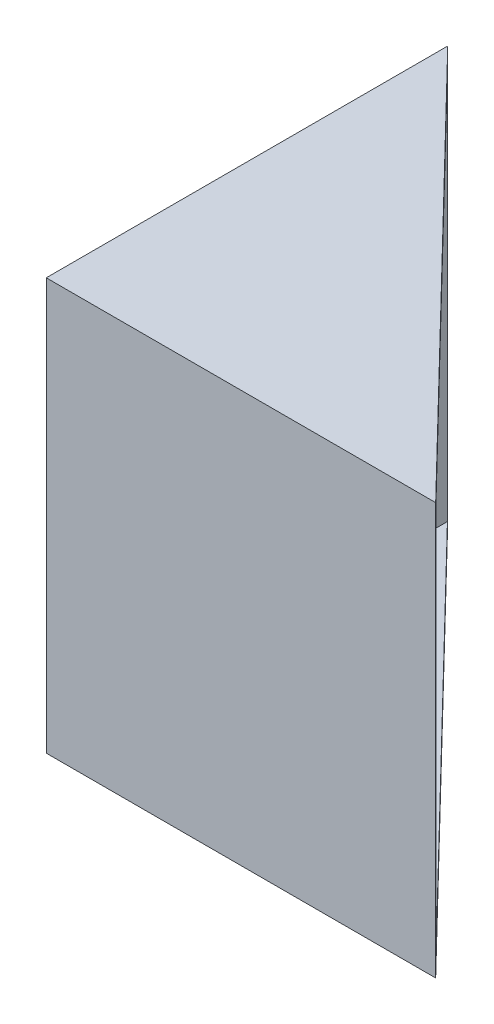
SolidWorks part; units mm, degrees
ref_plane "Front Plane" through (0, 0, 0) normal (0, 0, 1) x (1, 0, 0)
ref_plane "Top Plane" through (0, 0, 0) normal (0, 1, 0) x (1, 0, 0)
ref_plane "Right Plane" through (0, 0, 0) normal (1, 0, 0) x (0, 0, -1)
sketch "Sketch1" plane through (0, 0, 0) normal (0, 1, 0) x (1, 0, 0)
  line L0 (-22.5, -22.5) -> (53.1685, -22.5)
  line L1 (-22.5, -22.5) -> (-22.5, 55.5143)
  line L2 (-22.5, 55.5143) -> (53.1685, -22.5)
  dimension "D2" = 78.0143
extrude "Boss-Extrude1" add sketch "Sketch1" along normal blind 80
shell "Shell2" thickness 2
